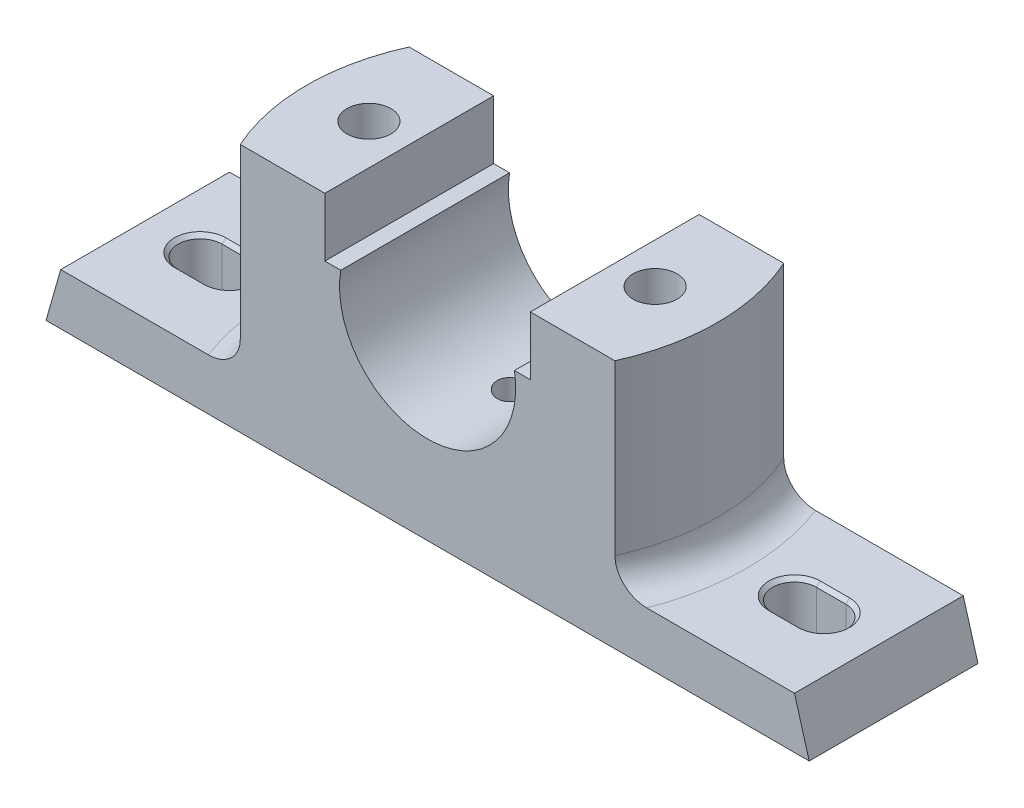
SolidWorks part; units mm, degrees
ref_plane "Front Plane" through (0, 0, 0) normal (0, 0, 1) x (1, 0, 0)
ref_plane "Top Plane" through (0, 0, 0) normal (0, 1, 0) x (1, 0, 0)
ref_plane "Right Plane" through (0, 0, 0) normal (1, 0, 0) x (0, 0, -1)
sketch "Sketch1" plane through (0, 0, 0) normal (0, 0, 1) x (1, 0, 0)
  line L0 (-104, 0) -> (104, 0)
  line L1 (-104, 0) -> (-99.9856, 14)
  line L2 (104, 0) -> (99.9856, 14)
  line L3 (0, 115.8251) -> (0, -90.3557) construction
  line L4 (-99.9856, 14) -> (99.9856, 14)
  dimension "D1" = 208
  dimension "D2" = 104
  dimension "D3" = 106
  dimension "D4" = 106
  dimension "D5" = 14
  dimension "D6" = 14
extrude "Boss-Extrude2" add sketch "Sketch1" along normal mid plane 46
sketch "Sketch3" plane through (0, 14, 0) normal (0, 1, 0) x (1, 0, 0)
  line L0 (99.9856, 23) -> (-99.9856, 23) construction
  line L1 (51.0588, 23) -> (-51.0588, 23)
  line L2 (99.9856, -23) -> (-99.9856, -23) construction
  line L3 (51.0588, -23) -> (-51.0588, -23)
  line L4 (-51.0588, 23) -> (51.0588, 23)
  line L5 (51.0588, -23) -> (-51.0588, -23)
  arc A0 (-51.0588, 23) -> (-51.0588, -23) centre (0, 0) ccw
  arc A1 (51.0588, -23) -> (51.0588, 23) centre (0, 0) ccw
  line M1 (99.9856, 23) -> (-99.9856, 23)
  line M3 (-99.9856, -23) -> (99.9856, -23)
  dimension "D1" = 112
extrude "Boss-Extrude3" add sketch "Sketch3" along normal blind 54 contours A1 A0 M3 M1
ref_plane "Plane1" through (0, 0, 0) normal (0, 0, 1) x (1, 0, 0)
sketch "Sketch5" plane through (0, 0, 0) normal (0, 0, 1) x (1, 0, 0)
  line L0 (0, 0) -> (0, 81.1511) construction
  line L1 (-28, 75.2693) -> (-28, 52)
  line L2 (-28, 52) -> (-23.6643, 52)
  line L3 (28, 52) -> (23.6643, 52)
  line L4 (28, 75.2693) -> (28, 52)
  line L5 (-51.0588, 68) -> (51.0588, 68) construction
  line L7 (-28, 75.2693) -> (28, 75.2693)
  arc A0 (-23.6643, 52) -> (23.6643, 52) centre (0, 48) ccw
  dimension "D2" = 16
  dimension "D3" = 24
  dimension "D1" = 56
  dimension "D4" = 4
extrude "Cut-Extrude1" cut sketch "Sketch5" against normal mid plane 54
sketch "Sketch6" plane through (0, 68, 0) normal (0, 1, 0) x (1, 0, 0)
  line L0 (0, 48.8413) -> (0, -35.3678) construction
  line L1 (-85, 0) -> (-77, 0) construction
  line L2 (-85, 6) -> (-77, 6)
  line L3 (-85, -6) -> (-77, -6)
  line L4 (77, 0) -> (85, 0) construction
  line L5 (77, 6) -> (85, 6)
  line L6 (77, -6) -> (85, -6)
  arc A2 (-85, 6) -> (-85, -6) centre (-85, 0) ccw
  arc A3 (-77, -6) -> (-77, 6) centre (-77, 0) ccw
  arc A4 (77, 6) -> (77, -6) centre (77, 0) ccw
  arc A5 (85, -6) -> (85, 6) centre (85, 0) ccw
  point P9 (-81, 0)
  point P14 (81, 0)
  dimension "D8" = 6
  dimension "D9" = 6
  dimension "D6" = 8
  dimension "D7" = 8
  dimension "D10" = 154
  dimension "D11" = 77
extrude "Cut-Extrude3" cut sketch "Sketch6" against normal through all
sketch "Sketch8" plane through (0, 0, 0) normal (0, -1, 0) x (1, 0, 0)
  line L0 (0, 23) -> (0, -23) construction
  line L1 (-104, 23) -> (104, 23) construction
  line L2 (-104, -23) -> (104, -23) construction
  line L3 (-51.1991, 0) -> (44.1256, 0) construction
  line L4 (52, -13) -> (26, -13)
  line L5 (-52, 13) -> (-26, 13)
  line L6 (-52, 13) -> (-52, -13)
  line L7 (-52, -13) -> (-26, -13)
  line L8 (-26, 13) -> (-26, -13)
  line L11 (26, 13) -> (26, -13)
  line L12 (52, 13) -> (26, 13)
  line L13 (52, 13) -> (52, -13)
  point P7 (-39, 0)
  point P16 (0, 0)
  point P17 (0, 0)
  dimension "D1" = 26
  dimension "D2" = 26
  dimension "D3" = 26
  dimension "D4" = 13
extrude "Cut-Extrude4" cut sketch "Sketch8" against normal blind 10
sketch "Sketch9" plane through (0, 0, 0) normal (0, -1, 0) x (1, 0, 0)
  line L0 (0, 59.9569) -> (0, -36.7152) construction
  circle A0 centre (-39, 0) radius 6
  circle A1 centre (39, 0) radius 6
  dimension "D1" = 12
  dimension "D2" = 39
extrude "Cut-Extrude5" cut sketch "Sketch9" against normal through all
sketch "Sketch10" plane through (0, 14, 0) normal (0, 1, 0) x (1, 0, 0)
  circle A0 centre (0, 0) radius 4
  dimension "D1" = 8
extrude "Cut-Extrude7" cut sketch "Sketch10" along normal blind 52
chamfer "Chamfer2" distance 1 angle 45 8 edges at (71, 14, 0) (81, 14, 6) (91, 14, 0) (81, 14, -6) (-91, 14, 0) (-81, 14, 6) (-71, 14, 0) (-81, 14, -6)
fillet "Fillet1" radius 8 2 edges at (-56, 14, 0) (56, 14, 0)
